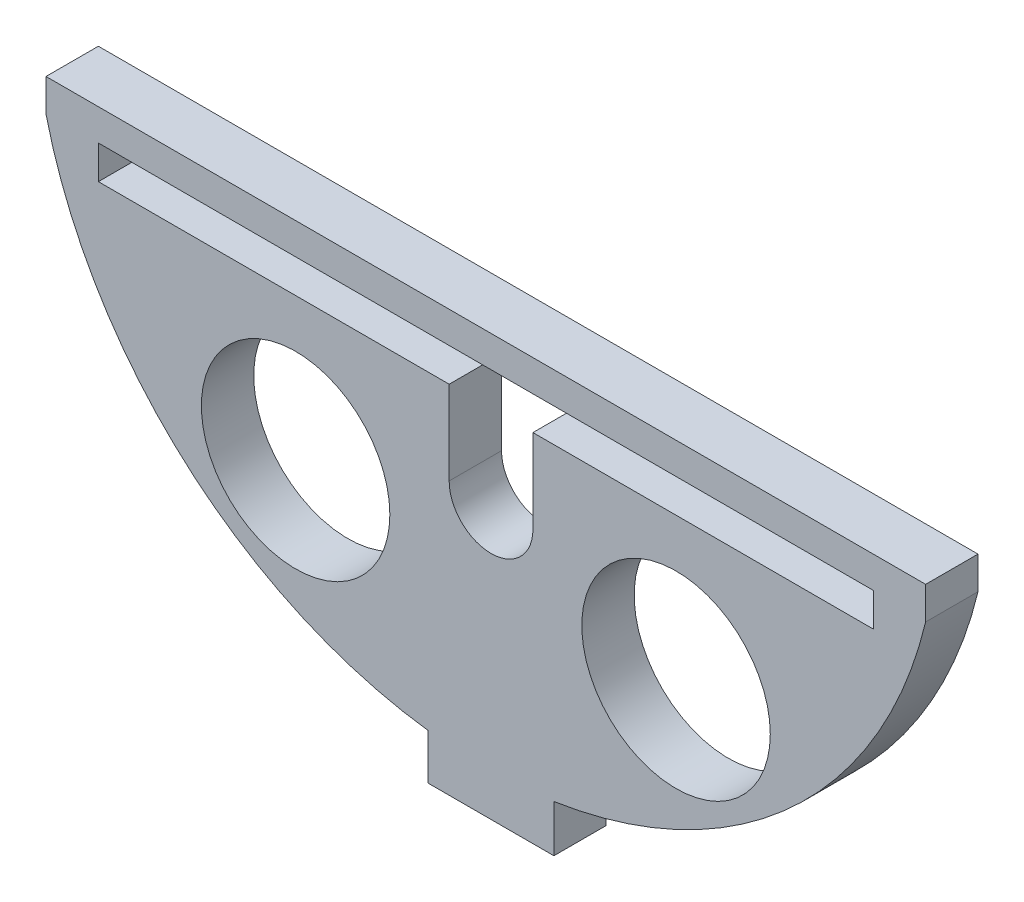
SolidWorks part; units mm, degrees
ref_plane "Alzado" through (0, 0, 0) normal (0, 0, 1) x (1, 0, 0)
ref_plane "Planta" through (0, 0, 0) normal (0, 1, 0) x (1, 0, 0)
ref_plane "Vista lateral" through (0, 0, 0) normal (1, 0, 0) x (0, 0, -1)
sketch "Croquis1" plane through (0, 0, 0) normal (0, 0, 1) x (1, 0, 0)
  line L1 (-37, -1.6) -> (37, -1.6)
  line L2 (-37, -1.6) -> (-37, 1.6)
  line L3 (-37, 1.6) -> (37, 1.6)
  line L4 (37, -1.6) -> (37, 1.6)
  line L5 (-37, -1.6) -> (37, 1.6) construction
  line L6 (-37, 1.6) -> (37, -1.6) construction
  line L7 (-3.5, -9.6) -> (-3.5, -1.6)
  line L8 (4.5, -9.6) -> (4.5, -1.6)
  line L10 (-42, 4.6) -> (42, 4.6)
  line L11 (-42, 4.6) -> (-42, 1.4886)
  line L12 (-40.0475, -4.6) -> (-5.5, -4.6)
  line L13 (42, 4.6) -> (42, 1.4886)
  line L14 (-42, 4.6) -> (40.1297, -4.3952) construction
  line L15 (-40.1297, -4.3952) -> (42, 4.6) construction
  line L16 (-3.5, -4.6) -> (4.5, -4.6)
  line L17 (6.5, -4.6) -> (40.0475, -4.6)
  line L18 (-5.5, -9.6) -> (-5.5, -4.6)
  line L19 (6.5, -9.6) -> (6.5, -4.6)
  circle A0 centre (0.5, -9.6) radius 4
  arc A1 (4.5, -8.1639) -> (-3.5, -8.1639) centre (0.5, -9.6) ccw
  arc A3 (-5.5, -9.6) -> (6.5, -9.6) centre (0.5, -9.6) ccw
  arc A4 (4.5, -5.1279) -> (-3.5, -5.1279) centre (0.5, -9.6) ccw
  arc A5 (-42, 1.4886) -> (42, 1.4886) centre (0, 11.6) ccw
  point P0 (0, 0)
  point P13 (0, 0)
  dimension "D3" = 8
  dimension "D8" = 8.5
  dimension "D9" = 12
  dimension "D10" = 30
  dimension "D1" = 74
  dimension "D2" = 3.2
  dimension "D4" = 37.5
  dimension "D5" = 3
  dimension "D6" = 5
  dimension "D7" = 8
extrude "Saliente-Extruir1" add sketch "Croquis1" along normal blind 5 contours L18 A3 L19 L17 L13 L10 L11 L12 A0 L7 L1 L2 L3 L4 L8
ref_plane "Plano1" through (0, -32.4, 0) normal (0, 1, 0) x (1, 0, 0)
sketch "Croquis3" plane through (0, 0, 0) normal (0, 0, 1) x (1, 0, 0)
  line L1 (0, 0) -> (0, 30.8986) construction
  line L4 (6.5, -4.6) -> (40.0475, -4.6)
  line L5 (-40.0475, -4.6) -> (-5.5, -4.6)
  line L8 (6.5, -9.6) -> (6.5, -4.6)
  line L9 (-5.5, -9.6) -> (-5.5, -4.6)
  line L14 (6.5, -4.6) -> (40.0475, -4.6)
  line L15 (42, 4.6) -> (42, 1.4886)
  line L16 (-40.0475, -4.6) -> (-5.5, -4.6)
  line L17 (-42, 4.6) -> (-42, 1.4886)
  line L18 (-5.5, -31.2485) -> (-5.5, -35.6)
  line L19 (-5.5, -35.6) -> (6.5, -35.6)
  line L20 (6.5, -35.6) -> (6.5, -31.1082)
  arc A0 (-40.0475, -4.6) -> (-13.6103, -29.4) centre (0, 11.6) ccw
  circle A1 centre (-18.1646, -15.2119) radius 9
  circle A2 centre (18.1646, -15.2119) radius 9
  arc A4 (-5.5, -9.6) -> (6.5, -9.6) centre (0.5, -9.6) ccw
  arc A5 (-13.6103, -29.4) -> (-5.5, -31.2485) centre (0, 11.6) ccw
  arc A6 (-42, 1.4886) -> (-5.5, -31.2485) centre (0, 11.6) ccw
  arc A7 (6.5, -31.1082) -> (40.0475, -4.6) centre (0, 11.6) ccw
  arc A8 (6.5, -31.1082) -> (42, 1.4886) centre (0, 11.6) ccw
  dimension "D1" = 18
  dimension "D2" = 43.2
  dimension "D3" = 6
  dimension "D6" = 40.0475
  dimension "D7" = 42
  dimension "D8" = 13.6103
  dimension "D4" = 0.5
  dimension "D5" = 18.1646
  dimension "D9" = 18.1646
  dimension "D10" = 1.4886
  dimension "D11" = 4.6
  dimension "D12" = 4
  dimension "D14" = 9.6
  dimension "D15" = 15.2119
extrude "Saliente-Extruir2" add sketch "Croquis3" along normal up to surface (5 mm away) contours A0 A5 L4 L8 A4 L9 L5 A2 A1 up to face at (0.25, -3.3, 5)
